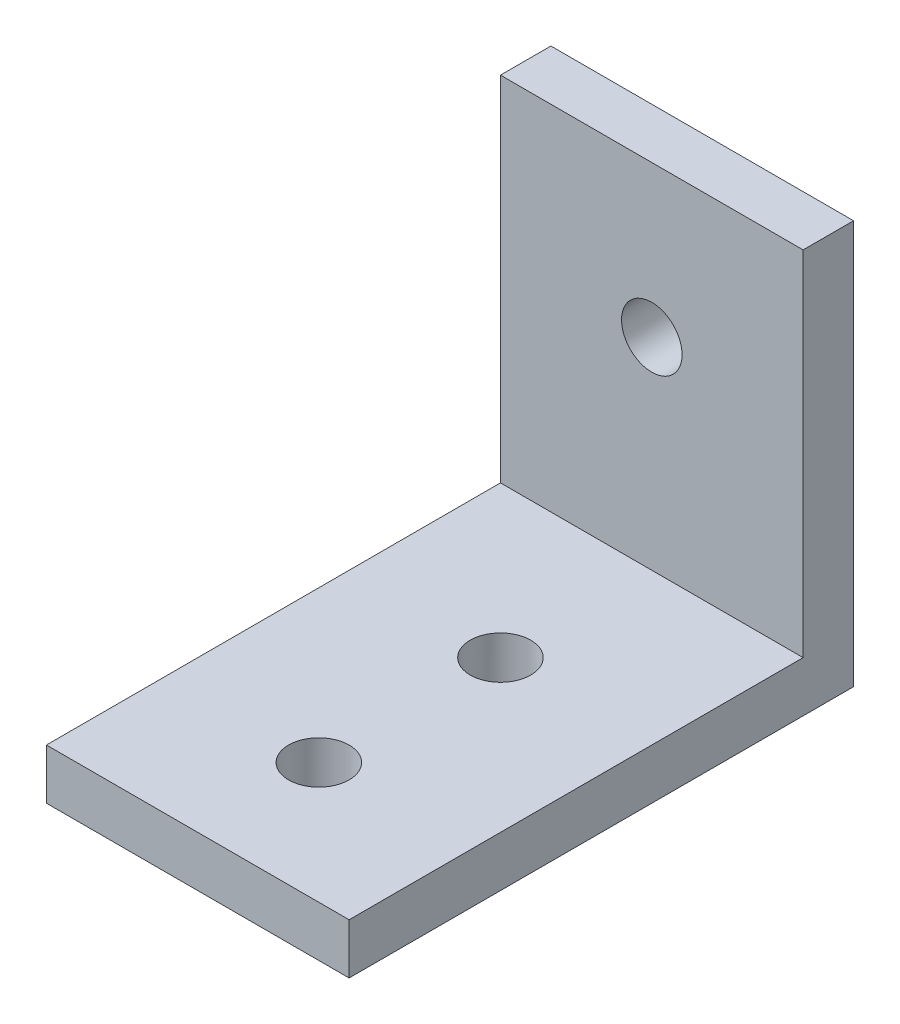
SolidWorks part; units mm, degrees
ref_plane "前视基准面" through (0, 0, 0) normal (0, 0, 1) x (1, 0, 0)
ref_plane "上视基准面" through (0, 0, 0) normal (0, 1, 0) x (1, 0, 0)
ref_plane "右视基准面" through (0, 0, 0) normal (1, 0, 0) x (0, 0, -1)
sketch "草图1" plane through (0, 0, 0) normal (0, 1, 0) x (1, 0, 0)
  line L0 (-15, 0) -> (15, 0)
  line L1 (15, 0) -> (15, -50)
  line L2 (15, -50) -> (-15, -50)
  line L3 (-15, -50) -> (-15, 0)
extrude "凸台-拉伸1" add sketch "草图1" along normal blind 5
sketch "草图2" plane through (0, 0, 0) normal (0, 0, 1) x (1, 0, 0)
  line L0 (-15, 0) -> (15, 0)
  line L1 (15, 0) -> (15, 40)
  line L2 (15, 40) -> (-15, 40)
  line L3 (-15, 40) -> (-15, 0)
extrude "凸台-拉伸2" add sketch "草图2" along normal blind 5
sketch "草图3" plane through (0, 0, 0) normal (0, 1, 0) x (1, 0, 0)
  circle A0 centre (0, -20) radius 3
  circle A1 centre (0, -38) radius 3
extrude "切除-拉伸1" cut sketch "草图3" along normal through all
sketch "草图4" plane through (0, 0, 0) normal (0, 0, 1) x (1, 0, 0)
  circle A0 centre (0, 25) radius 3
extrude "切除-拉伸2" cut sketch "草图4" along normal through all
